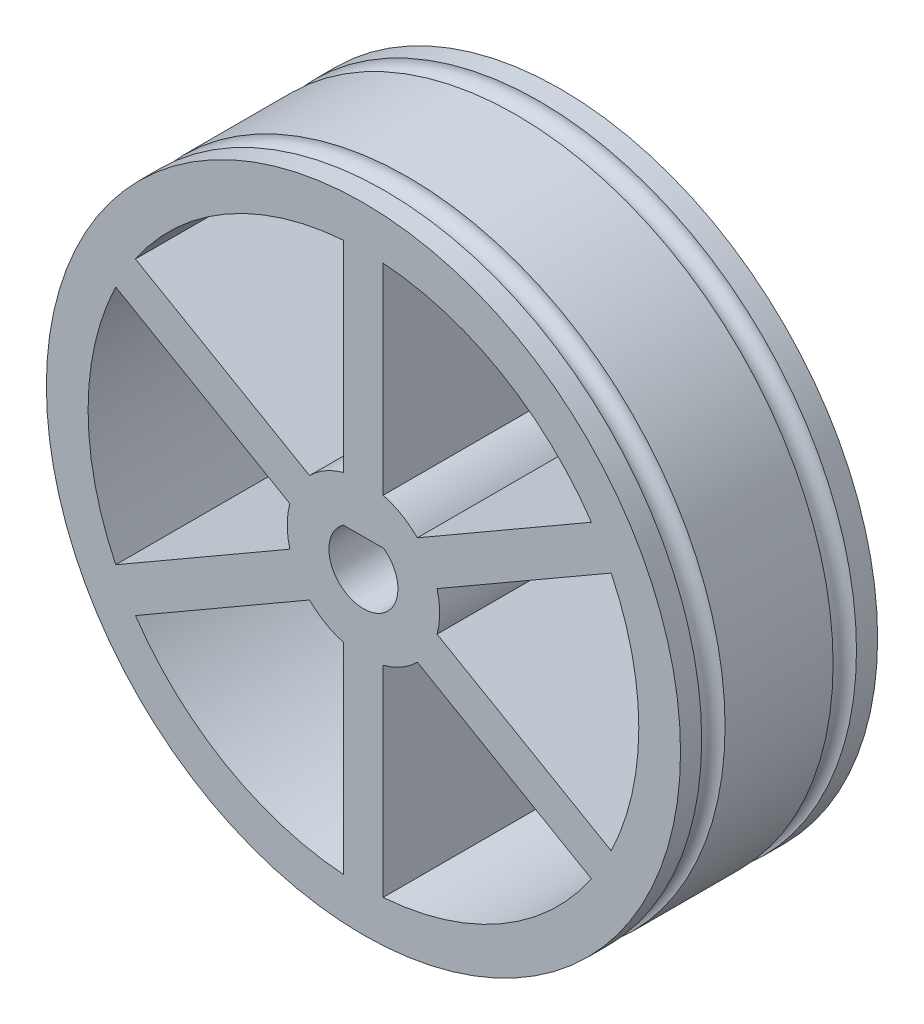
SolidWorks part; units mm, degrees
ref_plane "Front Plane" through (0, 0, 0) normal (0, 0, 1) x (1, 0, 0)
ref_plane "Top Plane" through (0, 0, 0) normal (0, 1, 0) x (1, 0, 0)
ref_plane "Right Plane" through (0, 0, 0) normal (1, 0, 0) x (0, 0, -1)
sketch "Sketch1" plane through (0, 0, 0) normal (0, 0, 1) x (1, 0, 0)
  circle A0 centre (0, 0) radius 24.13
  circle A1 centre (0, 0) radius 20.955
  circle A2 centre (0, 0) radius 2.625
  circle A3 centre (0, 0) radius 5.8
  dimension "D1" = 48.26
  dimension "D2" = 3.175
  dimension "D3" = 5.25
  dimension "D4" = 3.175
extrude "Boss-Extrude1" add sketch "Sketch1" along normal blind 15 contours A0 A1 | A3 A2
sketch "Sketch3" plane through (0, 0, 0) normal (0, 0, -1) x (-1, 0, 0)
  line L0 (0, 0) -> (0, 2.625) construction
  line L1 (1.5, 2.625) -> (-1.5, 2.625)
  line L2 (0, 2.625) -> (0, 20.955) construction
  line L3 (1.5, 20.955) -> (-1.5, 20.955)
  line L4 (-1.5, 20.955) -> (-1.5, 2.625)
  line L5 (1.5, 20.955) -> (1.5, 2.625)
  circle A0 centre (0, 0) radius 2.625 construction
  circle A1 centre (0, 0) radius 20.955 construction
  point P7 (0, 2.625)
  point P14 (0, 20.955)
  dimension "D1" = 3
  dimension "D2" = 3
extrude "Boss-Extrude3" add sketch "Sketch3" against normal up to surface (15 mm away) up to face at (2.625, 0, 15)
pattern_circular "CirPattern1" count 6 over 360 about axis through (0, 0, 0) along (0, 0, 1) of "Boss-Extrude3"
sketch "Sketch4" plane through (0, 0, 0) normal (1, 0, 0) x (0, 0, -1)
  line L0 (0, 0) -> (0, 24.13) construction
  line L1 (0, 24.13) -> (-15, 24.13) construction
  line L2 (-2.5, 24.13) -> (-12.5, 24.13) construction
  line L3 (0, 0) -> (-22.4846, 0) construction
  circle A0 centre (-12.5, 24.13) radius 0.89
  circle A1 centre (-2.5, 24.13) radius 0.89
  point P9 (-7.5, 24.13)
  dimension "D3" = 1.78
  dimension "D1" = 15
  dimension "D2" = 10
  dimension "D4" = 24.13
  dimension "D5" = 2.5
revolve "Cut-Revolve1" cut sketch "Sketch4" angle 360 about L3
sketch "Sketch5" plane through (0, 0, 15) normal (0, 0, 1) x (1, 0, 0)
  line L0 (0, 0) -> (0, 2.625) construction
  line L1 (-2.5, 2.625) -> (2.5, 2.625)
  line L2 (-2.5, 2.625) -> (-2.5, 2.125)
  line L3 (2.5, 2.625) -> (2.5, 2.125)
  line L4 (2.5, 2.125) -> (-2.5, 2.125)
  circle A0 centre (0, 0) radius 2.625 construction
  point P9 (0, 2.625)
  dimension "D1" = 5
  dimension "D2" = 0.5
extrude "Boss-Extrude4" add sketch "Sketch5" against normal up to surface (15 mm away) up to face at (6.401, 11.0869, 0)
ref_plane "Plane2" through (0, 0, 12.5) normal (0, 0, 1) x (1, 0, 0)
ref_plane "Plane3" through (0, 0, 2.5) normal (0, 0, -1) x (-1, 0, 0)
